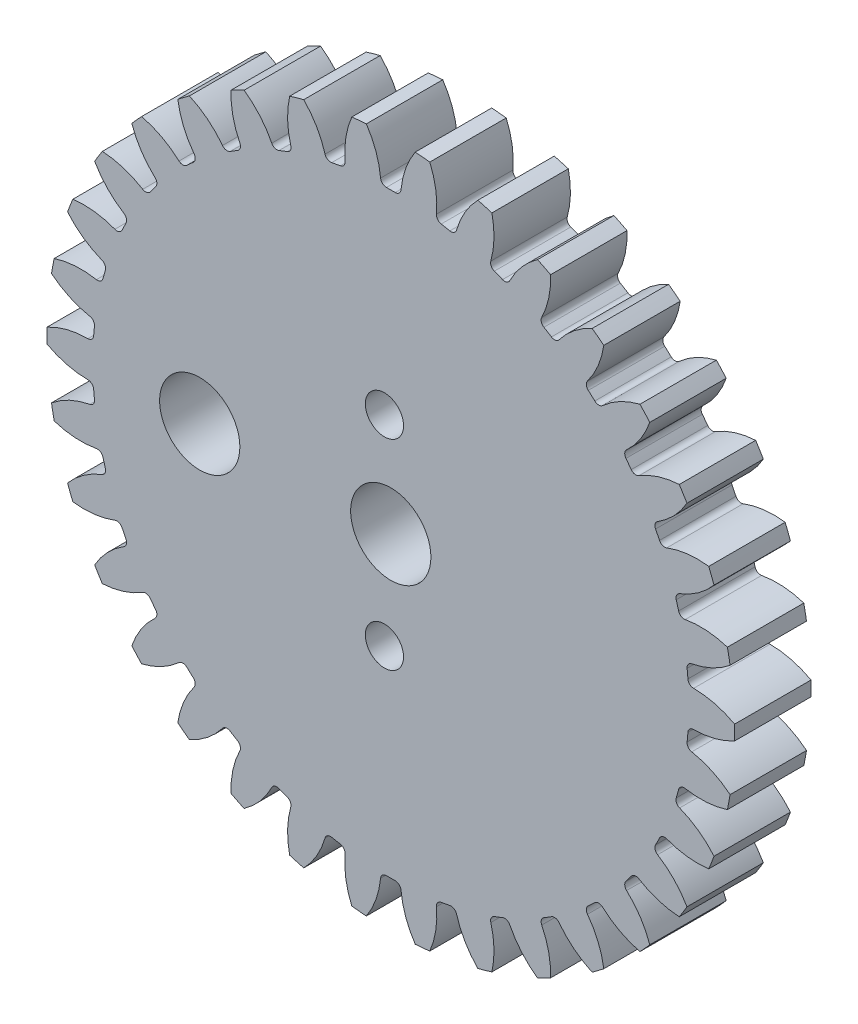
SolidWorks part; units mm, degrees
ref_plane "Front Plane" through (0, 0, 0) normal (0, 0, 1) x (1, 0, 0)
ref_plane "Top Plane" through (0, 0, 0) normal (0, 1, 0) x (1, 0, 0)
ref_plane "Right Plane" through (0, 0, 0) normal (1, 0, 0) x (0, 0, -1)
sketch "Sketch1" plane through (0, 0, 0) normal (0, 0, 1) x (1, 0, 0)
  circle A0 centre (0, 0) radius 8.5 construction
  circle A1 centre (0, 0) radius 9
  dimension "D1" = 17
  dimension "D2" = 18
extrude "Boss-Extrude1" add sketch "Sketch1" along normal mid plane 2
sketch "Sketch3" plane through (0, 0, 0) normal (0, 0, 1) x (1, 0, 0)
  line L0 (0, 9) -> (0, 0) construction
  line L1 (0, 0) -> (1.6537, 8.8468) construction
  line L2 (0, 0) -> (0.8304, 8.9616) construction
  line L3 (-0.2581, 7.7957) -> (0, 0) construction
  line L4 (-0.3926, 8.4909) -> (0.3926, 8.4909) construction
  line L5 (0.3926, 8.4909) -> (1.1743, 8.4185) construction
  line L6 (-0.5712, 8.9819) -> (0, 7.4124) construction
  circle A0 centre (0, 0) radius 8 construction
  arc A1 (0.2581, 7.7957) -> (-0.2581, 7.7957) centre (0, 0) ccw
  circle A2 centre (0, 0) radius 9 construction
  arc A3 (-0.6399, 8.9772) -> (-0.2581, 7.7957) centre (-2.5072, 7.7213) cw
  circle A5 centre (0, 0) radius 9 construction
  arc A6 (0.6399, 8.9772) -> (0.2581, 7.7957) centre (2.5072, 7.7213) ccw
  circle A7 centre (0, 0) radius 8.5 construction
  arc A9 (0.6399, 8.9772) -> (-0.6399, 8.9772) centre (0, 0) ccw
  dimension "D1" = 10.588
  dimension "D2" = 1
  dimension "D3" = 1.2
  dimension "D4" = 0.2
  dimension "D5" = 20
extrude "Cut-Extrude1" cut sketch "Sketch3" against normal through all both and the other way through all
fillet "Fillet1" radius 0.15 2 edges at (-0.2581, 7.7957, 0) (0.2581, 7.7957, 0)
pattern_circular "CirPattern1" count 34 over 360 about axis through (0, 0, 0) along (0, 0, 1) of "Fillet1", "Cut-Extrude1"
sketch "Sketch4" plane through (0, 0, 1) normal (0, 0, 1) x (1, 0, 0)
  circle A0 centre (0, 0) radius 1.05
  dimension "D1" = 2.1
extrude "Cut-Extrude2" cut sketch "Sketch4" against normal through all both
sketch "Sketch5" plane through (0, 0, 1) normal (0, 0, 1) x (1, 0, 0)
  line L0 (-5, 0) -> (0, 0) construction
  circle A0 centre (-5, 0) radius 1.05
  dimension "D1" = 2.1
  dimension "D2" = 5
extrude "Cut-Extrude3" cut sketch "Sketch5" against normal blind 10
sketch "Sketch6" plane through (0, 0, 1) normal (0, 0, 1) x (1, 0, 0)
  line L0 (1.1, 0) -> (-1.1, 0) construction
  circle A0 centre (-0.1663, -2.62) radius 0.5
  circle A2 centre (-0.1663, 2.62) radius 0.5
  dimension "D2" = 1
  dimension "D1" = 5.24
extrude "Cut-Extrude4" cut sketch "Sketch6" against normal through all contours A2 | A0
equation "\"module\"= 0.5mm"
equation "\"number of teeth\"= 34"
equation "\"pressure angle\"= 20"
equation "\"D1@Sketch1\"= \"module\" * \"number of teeth\""
equation "\"D2@Sketch1\"=(\"number of teeth\" + 2) * \"module\" "
equation "\"D1@Sketch3\"=360 / \"number of teeth\""
equation "\"D3@Sketch3\"= \"module\"  * if( \"module\" => 1.25,2.25,2.4)"
equation "\"D5@Sketch3\"=\"pressure angle\""
equation "\"D1@Fillet1\"=0.3 * \"module\""
equation "\"D1@CirPattern1\"=\"number of teeth\""
equation "\"D1@Chamfer1\"=\"module\""
